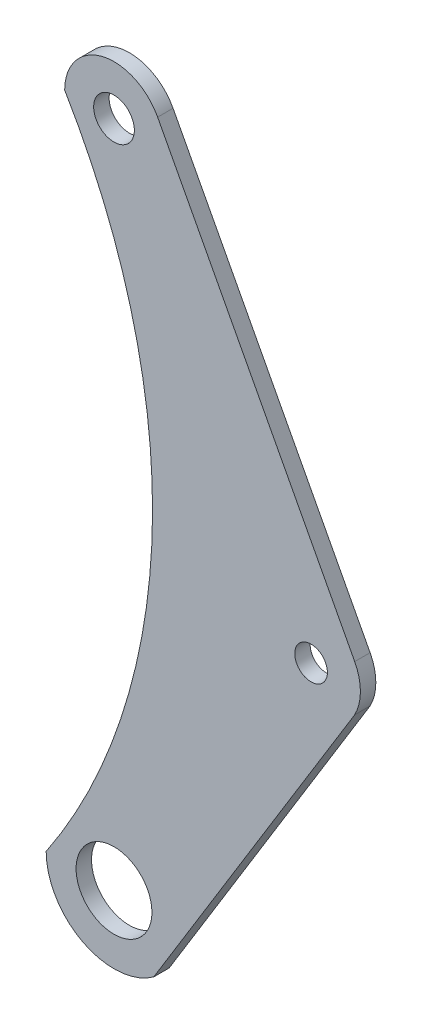
SolidWorks part; units mm, degrees
material "6061-T6 (SS)"
ref_plane "X-Y Datum" through (0, 0, 0) normal (0, 0, 1) x (1, 0, 0)
ref_plane "X-Z Datum" through (0, 0, 0) normal (0, 1, 0) x (1, 0, 0)
ref_plane "Y-Z Datum" through (0, 0, 0) normal (1, 0, 0) x (0, 0, -1)
sketch "Sketch1" plane through (0, 0, 0) normal (0, 0, 1) x (1, 0, 0)
  line L0 (0, 0) -> (0, 137.668) construction
  line L1 (0, 137.668) -> (40.5829, 60.8625) construction
  line L2 (40.5829, 60.8625) -> (0, 0) construction
  line L3 (-13.97, 0) -> (-10.16, 137.668)
  line L4 (8.9831, 142.4145) -> (49.566, 65.6091)
  line L5 (49.566, 56.116) -> (8.1778, -11.3263)
  circle A0 centre (0, 0) radius 7.8105
  circle A1 centre (40.5829, 60.8625) radius 3.3655
  circle A2 centre (0, 137.668) radius 4.191
  arc A3 (-10.16, 137.668) -> (8.9831, 142.4145) centre (0, 137.668) cw
  arc A4 (49.566, 65.6091) -> (49.566, 56.116) centre (40.5829, 60.8625) cw
  arc A5 (8.1778, -11.3263) -> (-13.97, 0) centre (0, 0) cw
  arc A6 (-10.16, 137.668) -> (-13.97, 0) centre (-120.8325, 71.8442) cw
  circle A7 centre (0, 0) radius 11.5718
  point P16 (50.7429, 60.8625)
  dimension "D4" = 15.621
  dimension "D5" = 6.731
  dimension "D6" = 8.382
  dimension "D7" = 13.97
  dimension "D8" = 10.16
  dimension "D9" = 10.16
  dimension "D10" = 23.1436
  dimension "D12" = 128.7679
  dimension "D1" = 137.668
  dimension "D2" = 86.868
  dimension "D3" = 73.152
  dimension "D11" = 125.83
extrude "Boss-Extrude1" add sketch "Sketch1" along normal blind 3.175 contours A3 A6 A5 L5 A4 L4 A2 A1 A0 | A6 A7 A0
